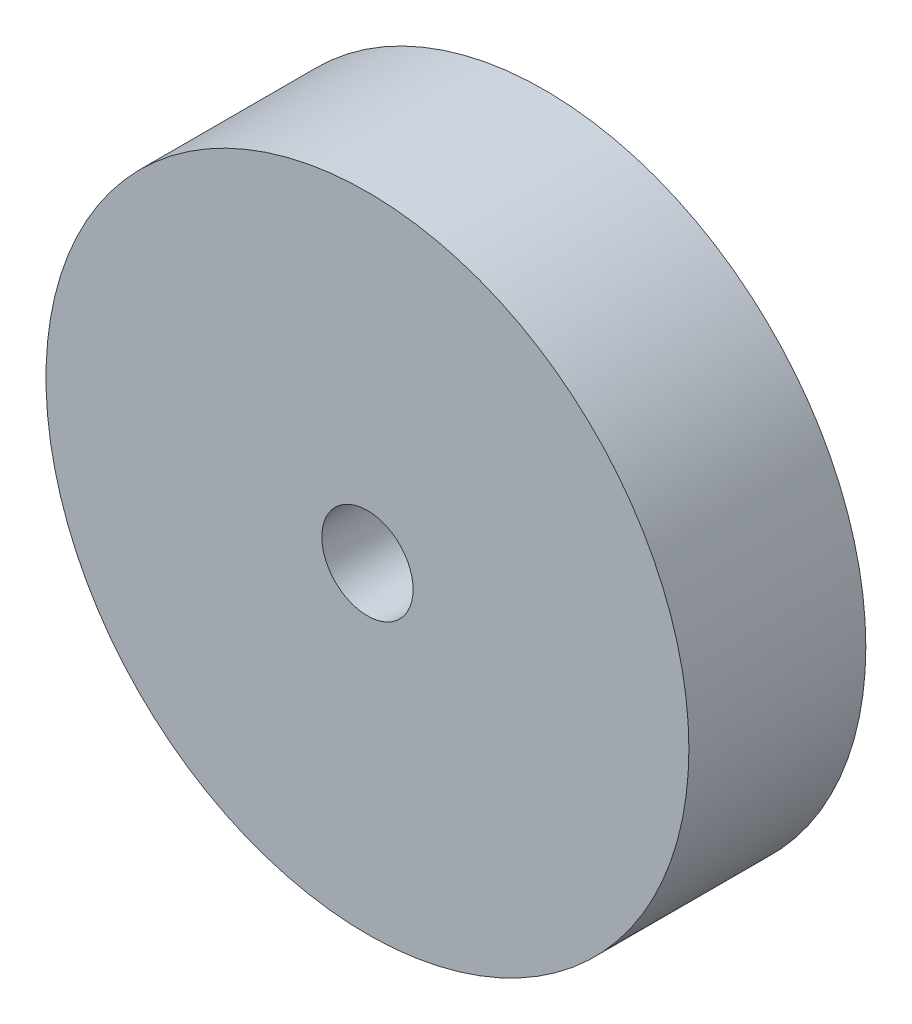
SolidWorks part; units mm, degrees
ref_plane "Front Plane" through (0, 0, 0) normal (0, 0, 1) x (1, 0, 0)
ref_plane "Top Plane" through (0, 0, 0) normal (0, 1, 0) x (1, 0, 0)
ref_plane "Right Plane" through (0, 0, 0) normal (1, 0, 0) x (0, 0, -1)
sketch "Sketch1" plane through (0, 0, 0) normal (0, 0, 1) x (1, 0, 0)
  circle A0 centre (0, 0) radius 1.775
  circle A1 centre (0, 0) radius 12.5
  dimension "D1" = 25
  dimension "D2" = 3.55
extrude "Boss-Extrude1" add sketch "Sketch1" along normal blind 6.88
